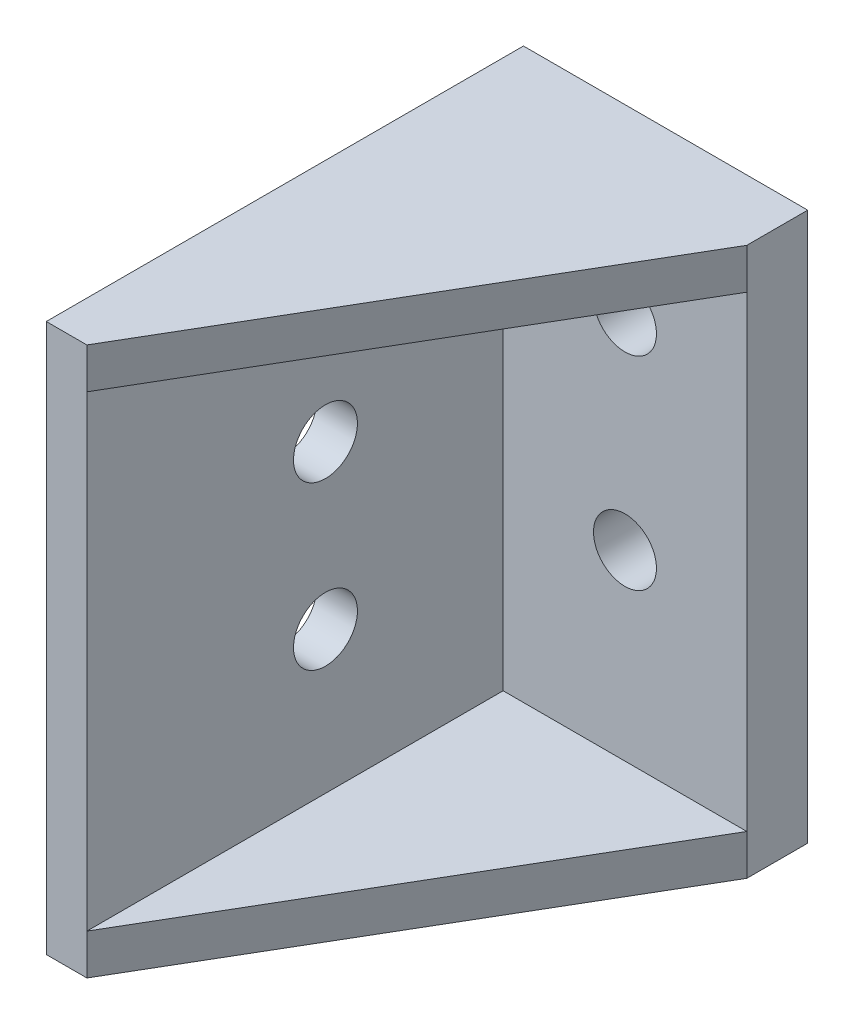
SolidWorks part; units mm, degrees
ref_plane "Front Plane" through (0, 0, 0) normal (0, 0, 1) x (1, 0, 0)
ref_plane "Top Plane" through (0, 0, 0) normal (0, 1, 0) x (1, 0, 0)
ref_plane "Right Plane" through (0, 0, 0) normal (1, 0, 0) x (0, 0, -1)
sketch "Sketch1" plane through (0, 0, 0) normal (0, 0, 1) x (1, 0, 0)
  line L1 (0, 0) -> (14, 0)
  line L2 (0, 0) -> (0, 25)
  line L3 (0, 25) -> (14, 25)
  line L4 (14, 0) -> (14, 25)
  circle A0 centre (8, 19) radius 1.55
  circle A1 centre (8, 9) radius 1.55
  dimension "D3" = 10
  dimension "D7" = 3.1
  dimension "D8" = 3.1
  dimension "D1" = 14
  dimension "D2" = 25
  dimension "D4" = 8
  dimension "D5" = 8
  dimension "D6" = 6
extrude "Boss-Extrude1" add sketch "Sketch1" along normal blind 3
sketch "Sketch3" plane through (0, 0, 3) normal (0, 0, 1) x (1, 0, 0)
  line L0 (0, 0) -> (0, 25)
  line L1 (0, 25) -> (14, 25)
  line L2 (14, 25) -> (14, 23)
  line L3 (14, 0) -> (14, 25) construction
  line L4 (14, 23) -> (2, 23)
  line L5 (2, 23) -> (2, 0)
  line L6 (0, 0) -> (14, 0) construction
  line L7 (2, 0) -> (0, 0)
  dimension "D1" = 2
  dimension "D2" = 2
extrude "Boss-Extrude2" add sketch "Sketch3" along normal blind 20.5
sketch "Sketch4" plane through (0, 0, 0) normal (-1, 0, 0) x (0, 0, 1)
  line L0 (0, 25) -> (0, 0) construction
  line L1 (23.5, 25) -> (0, 25) construction
  circle A0 centre (11.75, 15) radius 1.575
  circle A1 centre (11.75, 7) radius 1.575
  dimension "D1" = 3.15
  dimension "D2" = 3.15
  dimension "D3" = 8
  dimension "D4" = 11.75
  dimension "D5" = 11.75
  dimension "D6" = 10
extrude "Cut-Extrude1" cut sketch "Sketch4" against normal through all
sketch "Sketch5" plane through (0, 23, 0) normal (0, -1, 0) x (-1, 0, 0)
  line L0 (-14, -3) -> (-2, -23.5)
  line L1 (-2, -23.5) -> (-14, -23.5)
  line L2 (-14, -23.5) -> (-14, -3)
extrude "Cut-Extrude2" cut sketch "Sketch5" against normal blind 20.5
sketch "Sketch6" plane through (0, 0, 0) normal (0, -1, 0) x (-1, 0, 0)
  line L0 (-14, 0) -> (-14, -3)
  line L1 (-14, -3) -> (-2, -23.5)
  line L2 (-2, -23.5) -> (0, -23.5)
  line L3 (0, -23.5) -> (0, 0)
  line L4 (0, 0) -> (-14, 0)
extrude "Boss-Extrude3" add sketch "Sketch6" along normal blind 2
